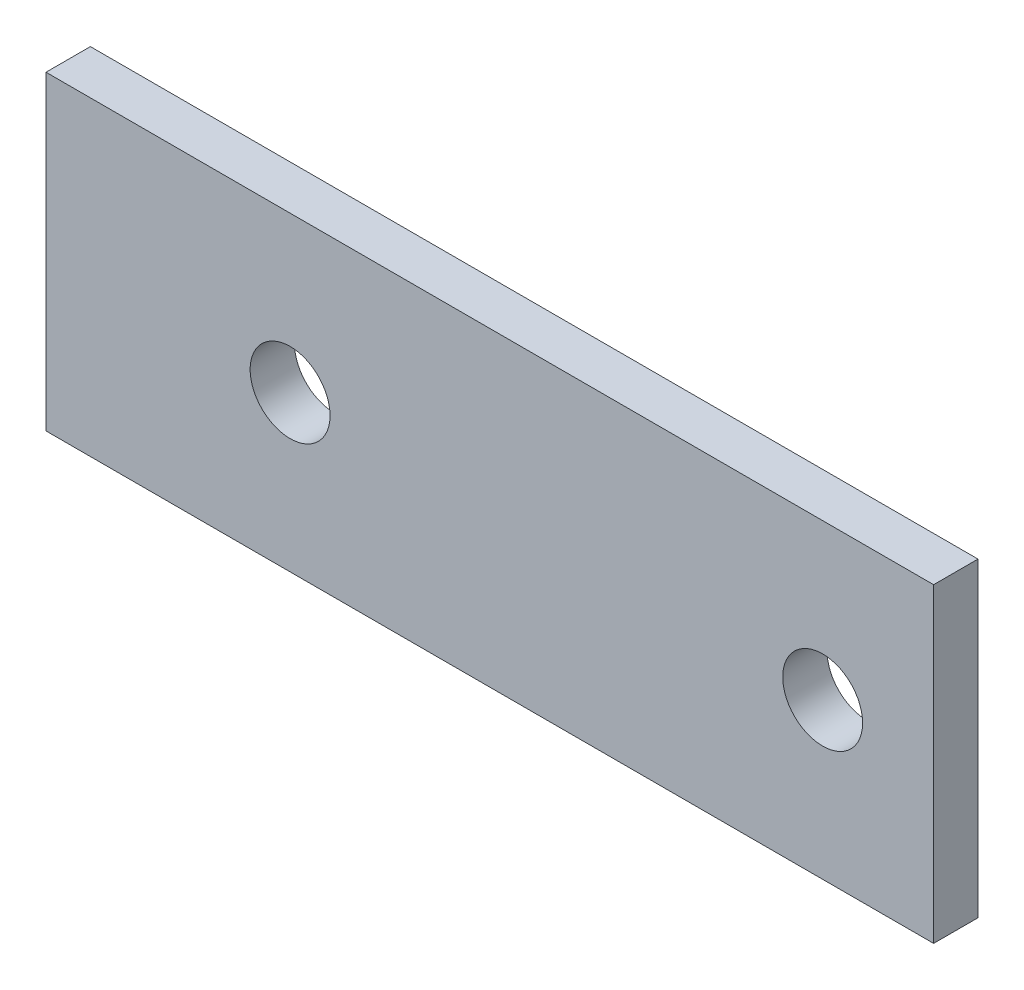
SolidWorks part; units mm, degrees
material "Plain Carbon Steel"
ref_plane "Front Plane" through (0, 0, 0) normal (0, 0, 1) x (1, 0, 0)
ref_plane "Top Plane" through (0, 0, 0) normal (0, 1, 0) x (1, 0, 0)
ref_plane "Right Plane" through (0, 0, 0) normal (1, 0, 0) x (0, 0, -1)
sketch "Sketch1" plane through (0, 0, 0) normal (0, 0, 1) x (1, 0, 0)
  line L1 (-100, 35) -> (100, 35)
  line L2 (-100, 35) -> (-100, -35)
  line L3 (-100, -35) -> (100, -35)
  line L4 (100, 35) -> (100, -35)
  line L5 (-100, 35) -> (100, -35) construction
  line L6 (-100, -35) -> (100, 35) construction
  circle A0 centre (75, 0) radius 9
  circle A1 centre (-45, 0) radius 9
  point P0 (0, 0)
  point P10 (100, 0)
  dimension "D3" = 18
  dimension "D4" = 18
  dimension "D5" = 25
  dimension "D6" = 120
  dimension "D1" = 70
  dimension "D2" = 200
extrude "Boss-Extrude1" add sketch "Sketch1" along normal mid plane 10
